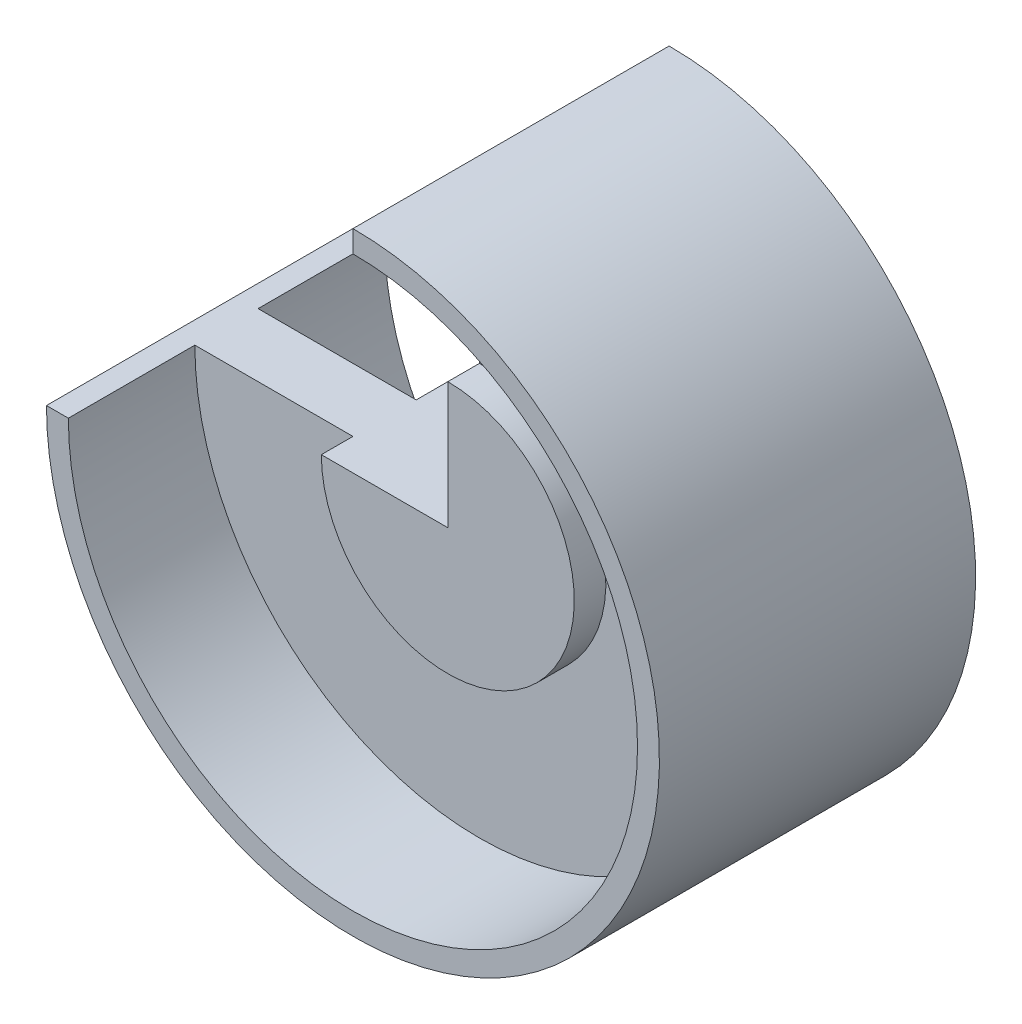
SolidWorks part; units mm, degrees
ref_plane "Front Plane" through (0, 0, 0) normal (0, 0, 1) x (1, 0, 0)
ref_plane "Top Plane" through (0, 0, 0) normal (0, 1, 0) x (1, 0, 0)
ref_plane "Right Plane" through (0, 0, 0) normal (1, 0, 0) x (0, 0, -1)
sketch "Sketch1" plane through (0, 0, 0) normal (1, 0, 0) x (0, 0, -1)
  line L0 (30000, 64.4447) -> (30000, -49935.5553) construction
  line L1 (-112.3179, 1.8413) -> (49887.6821, 1.8413) construction
  line L2 (20000, 1.8413) -> (40000, 1.8413)
  line L3 (40000, 1.8413) -> (40000, 20001.8413)
  line L4 (40000, 20001.8413) -> (35000, 20001.8413)
  line L5 (35000, 20001.8413) -> (35000, 45001.8413)
  line L6 (35000, 45001.8413) -> (55000, 45001.8413)
  line L7 (55000, 45001.8413) -> (55000, 48465.6606)
  line L8 (55000, 48465.6606) -> (5000, 48465.6606)
  line L9 (105.2875, 1.8413) -> (-49894.7125, 1.8413) construction
  line L10 (5000, 45001.8413) -> (5000, 48465.6606)
  line L11 (25000, 45001.8413) -> (5000, 45001.8413)
  line L12 (25000, 20001.8413) -> (25000, 45001.8413)
  line L13 (20000, 20001.8413) -> (25000, 20001.8413)
  line L14 (20000, 1.8413) -> (20000, 20001.8413)
  point P4 (0, 0)
  point P15 (30000, 48465.6606)
  point P20 (30000, 1.8413)
  point P21 (0, 0)
revolve "Revolve1" add sketch "Sketch1" angle 270 about L2
